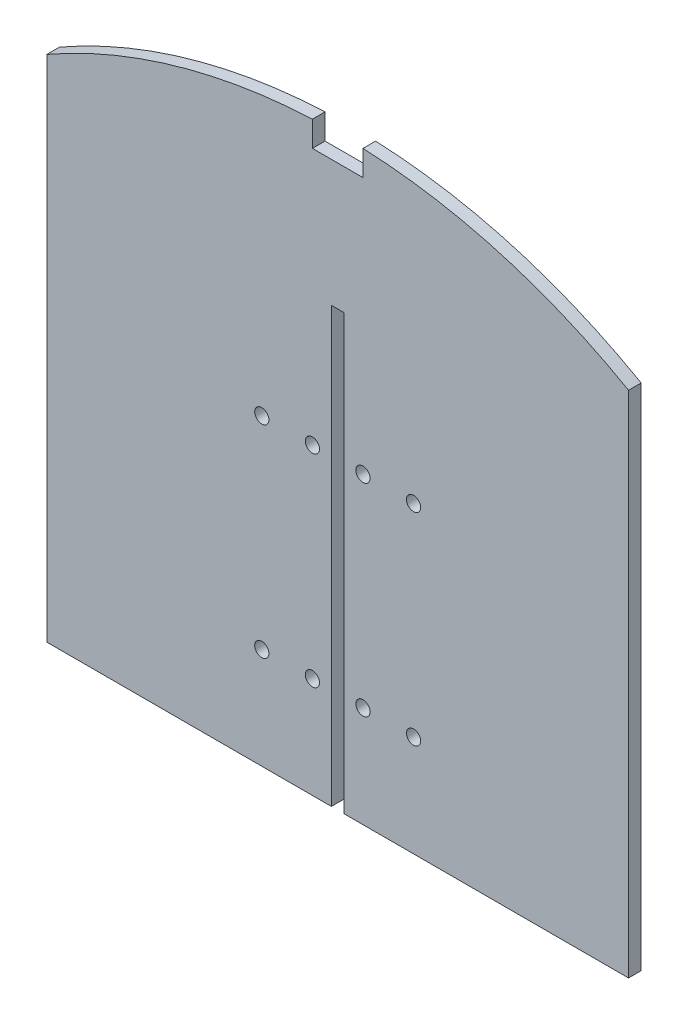
SolidWorks part; units mm, degrees
ref_plane "Front Plane" through (0, 0, 0) normal (0, 0, 1) x (1, 0, 0)
ref_plane "Top Plane" through (0, 0, 0) normal (0, 1, 0) x (1, 0, 0)
ref_plane "Right Plane" through (0, 0, 0) normal (1, 0, 0) x (0, 0, -1)
sketch "Sketch2" plane through (0, 0, 0) normal (0, 0, 1) x (1, 0, 0)
  line L0 (-294.386, 0) -> (-3.175, 0) construction
  line L1 (-3.175, 0) -> (-3.175, 217.9119)
  line L2 (0, 0) -> (0, 281.4119) construction
  line L3 (-12.7, 294.1119) -> (-12.7, 281.4119)
  line L4 (-12.7, 281.4119) -> (12.7, 281.4119)
  line L5 (12.7, 281.4119) -> (12.7, 294.1119)
  line L6 (-146.05, 255.6023) -> (-146.05, 0)
  line L7 (146.05, 255.6023) -> (146.05, 0)
  line L8 (-146.05, 0) -> (-3.175, 0)
  line L9 (-3.175, 217.9119) -> (3.175, 217.9119)
  line L10 (3.175, 217.9119) -> (3.175, 0)
  line L11 (3.175, 0) -> (294.386, 0) construction
  line L12 (3.175, 0) -> (146.05, 0)
  line L13 (-3.175, 0) -> (3.175, 0) construction
  arc A0 (294.386, 0) -> (12.7, 294.1119) centre (0, 0) ccw construction
  arc A1 (-146.05, 255.6023) -> (-12.7, 294.1119) centre (0, 0) cw
  arc A2 (-12.7, 294.1119) -> (-294.386, 0) centre (0, 0) ccw construction
  arc A3 (12.7, 294.1119) -> (146.05, 255.6023) centre (0, 0) cw
  point P16 (0, 217.9119)
  dimension "D1" = 588.772
  dimension "D3" = 25.4
  dimension "D2" = 292.1
  dimension "D4" = 12.7
  dimension "D5" = 6.35
  dimension "D6" = 63.5
extrude "Boss-Extrude2" add sketch "Sketch2" along normal blind 6.35 separate body
sketch "Sketch3" plane through (0, 0, 0) normal (0, 0, 1) x (1, 0, 0)
  line L0 (0, 50.8) -> (12.7, 50.8) construction
  line L1 (12.7, 50.8) -> (38.1, 50.8) construction
  line L2 (0, 0) -> (0, 189.439) construction
  circle A0 centre (12.7, 50.8) radius 3.5687
  circle A1 centre (38.1, 50.8) radius 3.5687
  circle A2 centre (12.7, 152.4) radius 3.5687
  circle A3 centre (38.1, 152.4) radius 3.5687
  circle A6 centre (-12.7, 50.8) radius 3.5687
  circle A7 centre (-38.1, 50.8) radius 3.5687
  circle A8 centre (-38.1, 152.4) radius 3.5687
  circle A9 centre (-12.7, 152.4) radius 3.5687
  dimension "D1" = 12.7
  dimension "E" = 7.1374
  dimension "D2" = 25.4
  dimension "D3" = 50.8
  dimension "D4" = 2
extrude "Cut-Extrude3" cut sketch "Sketch3" against normal blind 93.472 and the other way blind 148.336 contours A8 | A9 | A6 | A7 | A0 | A1 | A3 | A2
equation "\"D_inner\"= 23.18in"
